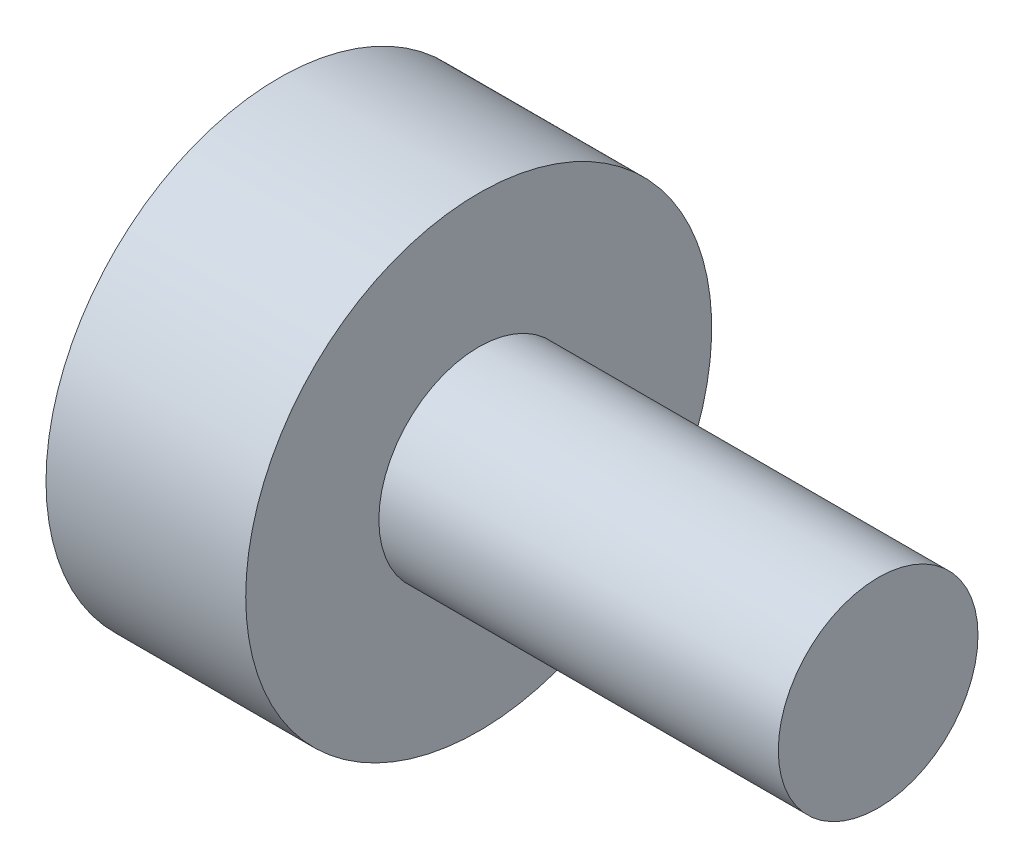
SolidWorks part; units mm, degrees
ref_plane "Спереди" through (0, 0, 0) normal (0, 0, 1) x (1, 0, 0)
ref_plane "Сверху" through (0, 0, 0) normal (0, 1, 0) x (1, 0, 0)
ref_plane "Справа" through (0, 0, 0) normal (1, 0, 0) x (0, 0, -1)
sketch "Эскиз1" plane through (0, 0, 0) normal (0, 0, 1) x (1, 0, 0)
  line L0 (0, 0) -> (100, 0)
  line L1 (0, 0) -> (0, 20)
  line L2 (0, 20) -> (10, 20)
  line L3 (10, 20) -> (10, 35)
  line L4 (10, 35) -> (40, 35)
  line L5 (40, 35) -> (40, 15)
  line L6 (40, 15) -> (100, 15)
  line L7 (100, 0) -> (100, 15)
revolve "Повернуть1" add sketch "Эскиз1" angle 360 about L0
sketch "Эскиз2" plane through (0, 0, 0) normal (1, 0, 0) x (0, 0, -1)
  circle A0 centre (0, 10) radius 5
extrude "Вырез-Вытянуть1" cut sketch "Эскиз2" along normal blind 20
